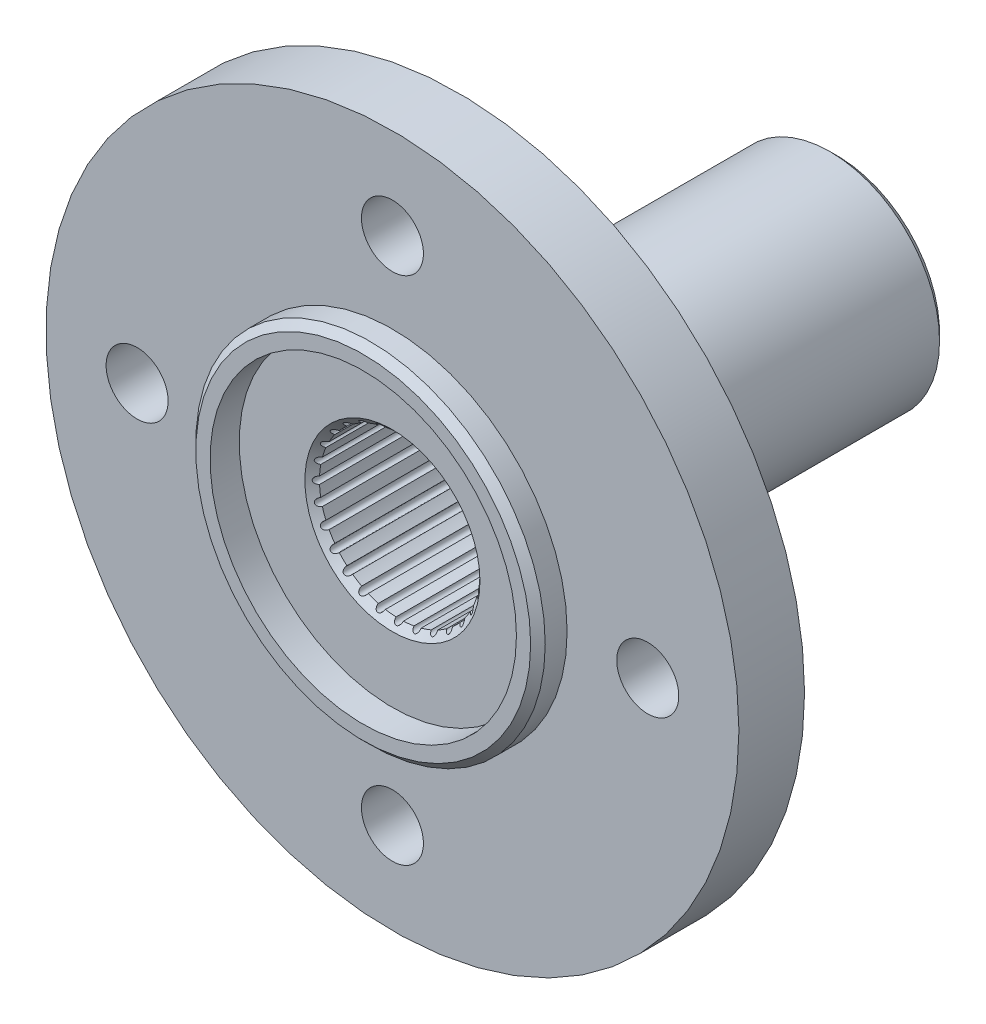
SolidWorks part; units mm, degrees
ref_plane "Ön Düzlem" through (0, 0, 0) normal (0, 0, 1) x (1, 0, 0)
ref_plane "Üst Düzlem" through (0, 0, 0) normal (0, 1, 0) x (1, 0, 0)
ref_plane "Sağ Düzlem" through (0, 0, 0) normal (1, 0, 0) x (0, 0, -1)
sketch "Sketch1" plane through (0, 0, 0) normal (0, 0, 1) x (1, 0, 0)
  circle A0 centre (0, 0) radius 47.5
  dimension "D1" = 95
extrude "Boss-Extrude1" add sketch "Sketch1" along normal blind 9
sketch "Sketch2" plane through (0, 0, 0) normal (0, 0, -1) x (-1, 0, 0)
  circle A0 centre (0, 0) radius 20
  dimension "D1" = 40
extrude "Boss-Extrude2" add sketch "Sketch2" along normal blind 22
sketch "Sketch3" plane through (0, 0, -22) normal (0, 0, -1) x (-1, 0, 0)
  circle A0 centre (0, 0) radius 15
  dimension "D1" = 30
extrude "Boss-Extrude3" add sketch "Sketch3" along normal blind 30
sketch "Sketch6" plane through (0, 0, -52) normal (0, 0, -1) x (-1, 0, 0)
  circle A0 centre (0, 0) radius 11
  dimension "D1" = 22
extrude "Cut-Extrude2" cut sketch "Sketch6" against normal blind 25
chamfer "Chamfer2" distance 1 1 edges at (-11, 0, -52)
sketch "Sketch9" plane through (0, 0, 9) normal (0, 0, 1) x (1, 0, 0)
  circle A0 centre (0, 35) radius 4.25
  circle A1 centre (35, 0) radius 4.25
  circle A2 centre (0, -35) radius 4.25
  circle A3 centre (-35, 0) radius 4.25
  point P12 (0, 0)
  dimension "D2" = 8.5
  dimension "D1" = 35
  dimension "D3" = 4
extrude "Cut-Extrude5" cut sketch "Sketch9" against normal up to next
chamfer "Chamfer3" distance 1 1 edges at (-15, 0, -52)
sketch "Sketch12" plane through (0, 0, 9) normal (0, 0, 1) x (1, 0, 0)
  circle A0 centre (0, 0) radius 23.95
  dimension "D1" = 47.9
extrude "Boss-Extrude4" add sketch "Sketch12" along normal blind 4
sketch "Sketch13" plane through (0, 0, 13) normal (0, 0, 1) x (1, 0, 0)
  circle A0 centre (0, 0) radius 21
  dimension "D1" = 42
extrude "Cut-Extrude6" cut sketch "Sketch13" against normal up to surface (4 mm away) up to face at (23.95, 0, 9)
chamfer "Chamfer4" distance 1 1 edges at (23.95, 0, 13)
sketch "Sketch8" plane through (0, 0, -52) normal (0, 0, -1) x (-1, 0, 0)
  circle A0 centre (0, 11) radius 0.5
  circle A1 centre (0, 0) radius 11 construction
  circle A2 centre (2.4477, 10.7242) radius 0.5
  circle A3 centre (4.7727, 9.9107) radius 0.5
  circle A4 centre (6.8584, 8.6001) radius 0.5
  circle A5 centre (8.6001, 6.8584) radius 0.5
  circle A6 centre (9.9107, 4.7727) radius 0.5
  circle A7 centre (10.7242, 2.4477) radius 0.5
  circle A8 centre (11, 0) radius 0.5
  circle A9 centre (10.7242, -2.4477) radius 0.5
  circle A10 centre (9.9107, -4.7727) radius 0.5
  circle A11 centre (8.6001, -6.8584) radius 0.5
  circle A12 centre (6.8584, -8.6001) radius 0.5
  circle A13 centre (4.7727, -9.9107) radius 0.5
  circle A14 centre (2.4477, -10.7242) radius 0.5
  circle A15 centre (0, -11) radius 0.5
  circle A16 centre (-2.4477, -10.7242) radius 0.5
  circle A17 centre (-4.7727, -9.9107) radius 0.5
  circle A18 centre (-6.8584, -8.6001) radius 0.5
  circle A19 centre (-8.6001, -6.8584) radius 0.5
  circle A20 centre (-9.9107, -4.7727) radius 0.5
  circle A21 centre (-10.7242, -2.4477) radius 0.5
  circle A22 centre (-11, 0) radius 0.5
  circle A23 centre (-10.7242, 2.4477) radius 0.5
  circle A24 centre (-9.9107, 4.7727) radius 0.5
  circle A25 centre (-8.6001, 6.8584) radius 0.5
  circle A26 centre (-6.8584, 8.6001) radius 0.5
  circle A27 centre (-4.7727, 9.9107) radius 0.5
  circle A28 centre (-2.4477, 10.7242) radius 0.5
  point P61 (0, 0)
  dimension "D1" = 1
  dimension "D2" = 28
extrude "Cut-Extrude4" cut sketch "Sketch8" against normal up to surface (25 mm away) up to face at (-11, 0, -27)
sketch "Sketch14" plane through (0, 0, -27) normal (0, 0, -1) x (-1, 0, 0)
  circle A0 centre (0, 0) radius 11
extrude "Cut-Extrude7" cut sketch "Sketch14" against normal through all
chamfer "Chamfer5" distance 1 1 edges at (11, 0, 9)
sketch "Sketch15" plane through (0, 0, -52) normal (0, 0, -1) x (-1, 0, 0)
  circle A1 centre (8.6001, 6.8584) radius 0.5
  circle A2 centre (8.6001, 6.8584) radius 0.5
  circle A3 centre (6.8584, 8.6001) radius 0.5
  circle A4 centre (6.8584, 8.6001) radius 0.5
  circle A5 centre (4.7727, 9.9107) radius 0.5
  circle A6 centre (4.7727, 9.9107) radius 0.5
  circle A7 centre (2.4477, 10.7242) radius 0.5
  circle A8 centre (2.4477, 10.7242) radius 0.5
  circle A9 centre (0, 11) radius 0.5
  circle A10 centre (0, 11) radius 0.5
  circle A11 centre (4.7727, -9.9107) radius 0.5
  circle A12 centre (4.7727, -9.9107) radius 0.5
  circle A13 centre (6.8584, -8.6001) radius 0.5
  circle A14 centre (6.8584, -8.6001) radius 0.5
  circle A15 centre (8.6001, -6.8584) radius 0.5
  circle A16 centre (8.6001, -6.8584) radius 0.5
  circle A17 centre (9.9107, -4.7727) radius 0.5
  circle A18 centre (9.9107, -4.7727) radius 0.5
  circle A19 centre (10.7242, -2.4477) radius 0.5
  circle A20 centre (10.7242, -2.4477) radius 0.5
  circle A21 centre (11, 0) radius 0.5
  circle A22 centre (11, 0) radius 0.5
  circle A23 centre (10.7242, 2.4477) radius 0.5
  circle A24 centre (10.7242, 2.4477) radius 0.5
  circle A25 centre (9.9107, 4.7727) radius 0.5
  circle A26 centre (9.9107, 4.7727) radius 0.5
  circle A27 centre (-10.7242, -2.4477) radius 0.5
  circle A28 centre (-10.7242, -2.4477) radius 0.5
  circle A29 centre (-9.9107, -4.7727) radius 0.5
  circle A30 centre (-9.9107, -4.7727) radius 0.5
  circle A31 centre (-8.6001, -6.8584) radius 0.5
  circle A32 centre (-8.6001, -6.8584) radius 0.5
  circle A33 centre (-6.8584, -8.6001) radius 0.5
  circle A34 centre (-6.8584, -8.6001) radius 0.5
  circle A35 centre (-4.7727, -9.9107) radius 0.5
  circle A36 centre (-4.7727, -9.9107) radius 0.5
  circle A37 centre (-2.4477, -10.7242) radius 0.5
  circle A38 centre (-2.4477, -10.7242) radius 0.5
  circle A39 centre (0, -11) radius 0.5
  circle A40 centre (0, -11) radius 0.5
  circle A41 centre (2.4477, -10.7242) radius 0.5
  circle A42 centre (2.4477, -10.7242) radius 0.5
  circle A43 centre (-2.4477, 10.7242) radius 0.5
  circle A44 centre (-2.4477, 10.7242) radius 0.5
  circle A45 centre (-4.7727, 9.9107) radius 0.5
  circle A46 centre (-4.7727, 9.9107) radius 0.5
  circle A47 centre (-6.8584, 8.6001) radius 0.5
  circle A48 centre (-6.8584, 8.6001) radius 0.5
  circle A49 centre (-8.6001, 6.8584) radius 0.5
  circle A50 centre (-8.6001, 6.8584) radius 0.5
  circle A51 centre (-9.9107, 4.7727) radius 0.5
  circle A52 centre (-9.9107, 4.7727) radius 0.5
  circle A53 centre (-10.7242, 2.4477) radius 0.5
  circle A54 centre (-10.7242, 2.4477) radius 0.5
  circle A55 centre (-11, 0) radius 0.5
  circle A56 centre (-11, 0) radius 0.5
  dimension "D1" = 0
  dimension "D2" = 0
  dimension "D3" = 0
  dimension "D4" = 0
  dimension "D5" = 0
  dimension "D6" = 0
  dimension "D7" = 0
  dimension "D8" = 0
  dimension "D9" = 0
  dimension "D10" = 0
  dimension "D11" = 0
  dimension "D12" = 0
  dimension "D13" = 0
  dimension "D14" = 0
  dimension "D15" = 0
  dimension "D16" = 0
  dimension "D17" = 0
  dimension "D18" = 0
  dimension "D19" = 0
  dimension "D20" = 0
  dimension "D21" = 0
  dimension "D22" = 0
  dimension "D23" = 0
  dimension "D24" = 0
  dimension "D25" = 0
  dimension "D26" = 0
  dimension "D27" = 0
  dimension "D28" = 0
extrude "Cut-Extrude8" cut sketch "Sketch15" against normal through all
sketch "Sketch16" plane through (0, 0, 0) normal (0, 1, 0) x (1, 0, 0)
  line L0 (47.5, 0) -> (-47.5, 0) construction
  line L1 (-20, 22) -> (-20, 0) construction
  line L2 (-15, 22) -> (-15, 37.3253) construction
  line L3 (-15, 51) -> (-15, 22) construction
  line L4 (-15, 22) -> (-20, 22)
  line L5 (20, 22) -> (-20, 22) construction
  line L6 (-20, 22) -> (-20, 0)
  line L7 (0, 0) -> (0, 9.9363) construction
  arc A0 (-15, 22) -> (-20, 0) centre (-65.9, 22) cw
revolve "Cut-Revolve1" cut sketch "Sketch16" angle 360 about L7
